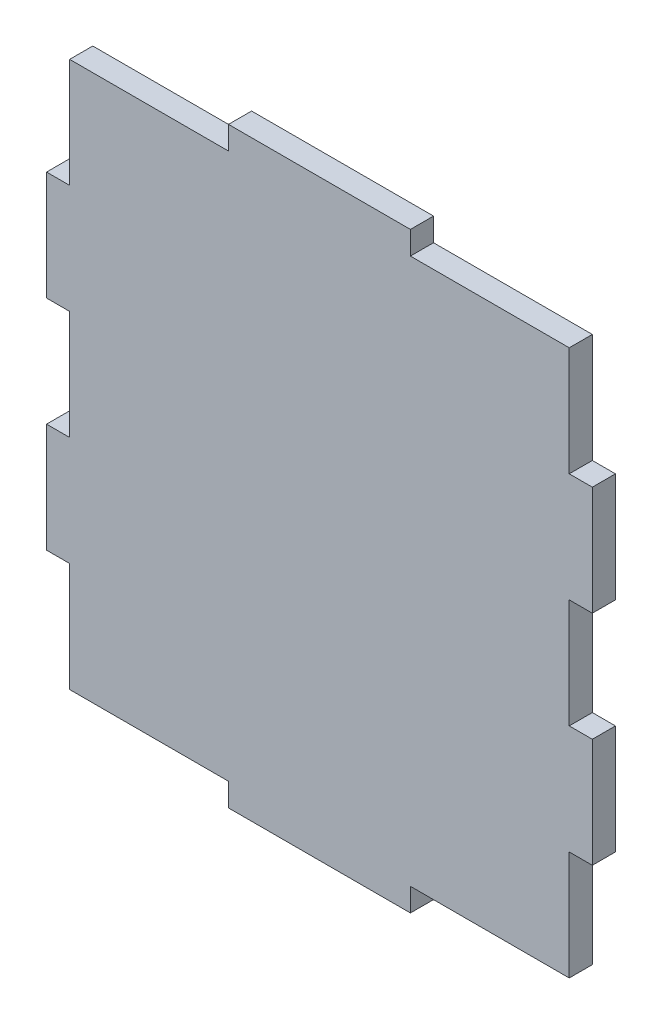
SolidWorks part; units mm, degrees
ref_plane "Front Plane" through (0, 0, 0) normal (0, 0, 1) x (1, 0, 0)
ref_plane "Top Plane" through (0, 0, 0) normal (0, 1, 0) x (1, 0, 0)
ref_plane "Right Plane" through (0, 0, 0) normal (1, 0, 0) x (0, 0, -1)
sketch "Sketch1" plane through (0, 0, 0) normal (0, 0, 1) x (1, 0, 0)
  line L0 (105.283, -33.1179) -> (105.283, -63.1179)
  line L1 (-38.367, 56.8821) -> (5.283, 56.8821)
  line L2 (105.283, -63.1179) -> (98.933, -63.1179)
  line L3 (98.933, 56.8821) -> (98.933, 26.8821)
  line L4 (-38.367, 56.8821) -> (-38.367, 26.8821)
  line L5 (98.933, -63.1179) -> (98.933, -93.1179)
  line L8 (55.283, 56.8821) -> (98.933, 56.8821)
  line L9 (5.283, 56.8821) -> (5.283, 63.2321)
  line L10 (5.283, 63.2321) -> (55.283, 63.2321)
  line L11 (55.283, 63.2321) -> (55.283, 56.8821)
  line L12 (-38.367, -63.1179) -> (-38.367, -93.1179)
  line L13 (-38.367, 26.8821) -> (-44.717, 26.8821)
  line L14 (-44.717, 26.8821) -> (-44.717, -3.1179)
  line L15 (-44.717, -3.1179) -> (-38.367, -3.1179)
  line L16 (-38.367, -3.1179) -> (-38.367, -33.1179)
  line L17 (-38.367, -33.1179) -> (-44.717, -33.1179)
  line L18 (-44.717, -33.1179) -> (-44.717, -63.1179)
  line L19 (-44.717, -63.1179) -> (-38.367, -63.1179)
  line L20 (-38.367, -93.1179) -> (5.283, -93.1179)
  line L21 (98.933, 26.8821) -> (105.283, 26.8821)
  line L22 (105.283, 26.8821) -> (105.283, -3.1179)
  line L23 (105.283, -3.1179) -> (98.933, -3.1179)
  line L24 (98.933, -3.1179) -> (98.933, -33.1179)
  line L25 (98.933, -33.1179) -> (105.283, -33.1179)
  line L29 (5.283, -93.1179) -> (5.283, -99.4679)
  line L30 (5.283, -99.4679) -> (55.283, -99.4679)
  line L31 (55.283, -99.4679) -> (55.283, -93.1179)
  line L32 (55.283, -93.1179) -> (98.933, -93.1179)
  point P5 (0, 0)
  point P41 (30.283, 4.4055)
  dimension "D2" = 6.35
  dimension "D3" = 6.35
  dimension "D4" = 30
  dimension "D5" = 150
  dimension "D6" = 30
  dimension "D7" = 30
  dimension "D8" = 30
  dimension "D9" = 30
  dimension "D10" = 6.35
  dimension "D11" = 6.35
  dimension "D12" = 6.35
  dimension "D13" = 30
  dimension "D14" = 30
  dimension "D15" = 30
  dimension "D16" = 30
  dimension "D17" = 30
extrude "Boss-Extrude1" add sketch "Sketch1" along normal blind 6.35
